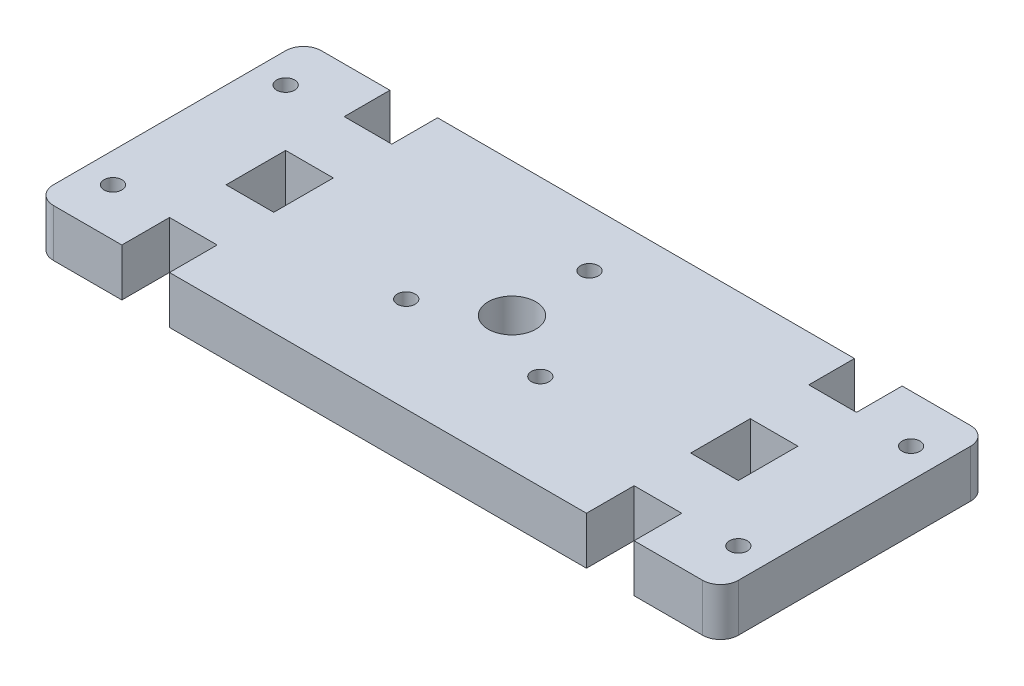
SolidWorks part; units mm, degrees
other "Markup1"
sketch "Sketch5" plane through (52.5, 8, -22.5) normal (0.067, 0.7574, -0.6495) x (-0.9884, -0.0385, -0.1469)
ref_plane "Front Plane" through (0, 0, 0) normal (0, 0, 1) x (1, 0, 0)
ref_plane "Top Plane" through (0, 0, 0) normal (0, 1, 0) x (1, 0, 0)
ref_plane "Right Plane" through (0, 0, 0) normal (1, 0, 0) x (0, 0, -1)
sketch "Sketch1" plane through (0, 0, 0) normal (0, 1, 0) x (1, 0, 0)
  line L0 (0, 0) -> (0, 1)
  line L1 (0, 1) -> (0, 25)
  line L3 (-57.5, -22.5) -> (57.5, -22.5)
  line L4 (-57.5, -22.5) -> (-57.5, 22.5)
  line L5 (-57.5, 22.5) -> (57.5, 22.5)
  line L6 (57.5, -22.5) -> (57.5, 22.5)
  line L7 (-57.5, -22.5) -> (57.5, 22.5) construction
  line L8 (-57.5, 22.5) -> (57.5, -22.5) construction
  circle A0 centre (0, 0) radius 50
  circle A1 centre (0, 0) radius 4
  circle A2 centre (0, 13) radius 1.5
  circle A3 centre (11.2583, -6.5) radius 1.5
  circle A4 centre (-11.2583, -6.5) radius 1.5
  dimension "D1" = 100
  dimension "D2" = 3
  dimension "D3" = 8
  dimension "D7" = 3
  dimension "D4" = 13
  dimension "D5" = 45
  dimension "125" = 115
extrude "Boss-Extrude1" add sketch "Sketch1" along normal blind 8
sketch "Sketch2" plane through (0, 8, 0) normal (0, 1, 0) x (1, 0, 0)
  line L1 (0, 0) -> (-35, 0)
  line L3 (-35, 0) -> (-35, 5)
  line L4 (-57.5, -22.5) -> (57.5, -22.5) construction
  line L12 (-35, 5) -> (-43, 5)
  line L13 (-35, 5) -> (-35, -5)
  line L18 (-35, -5) -> (-43, -5)
  line L27 (-43, 5) -> (-43, -5)
  line L55 (-35, 22.8298) -> (-43, 22.8298)
  line L56 (-35, 22.8298) -> (-35, 14.8298)
  line L57 (-35, 14.8298) -> (-43, 14.8298)
  line L58 (-43, 22.8298) -> (-43, 14.8298)
  line L63 (0, 0) -> (0, 22.8298)
  line L76 (43, 22.8298) -> (43, 14.8298)
  line L77 (35, 14.8298) -> (43, 14.8298)
  line L78 (35, 22.8298) -> (35, 14.8298)
  line L79 (35, 22.8298) -> (43, 22.8298)
  line L80 (43, 5) -> (43, -5)
  line L81 (35, -5) -> (43, -5)
  line L82 (35, 5) -> (35, -5)
  line L83 (35, 5) -> (43, 5)
  line L84 (35, 0) -> (35, 5)
  line L87 (-43, 0) -> (-49.5, 0)
  line L93 (-57.5, 0) -> (-56, 0)
  line L103 (-35, -22.5) -> (-43, -22.5)
  line L104 (-35, -22.5) -> (-35, -14.5)
  line L105 (-35, -14.5) -> (-43, -14.5)
  line L106 (-43, -22.5) -> (-43, -14.5)
  line L108 (35, -22.5) -> (43, -22.5)
  line L109 (35, -22.5) -> (35, -14.5)
  line L110 (35, -14.5) -> (43, -14.5)
  line L111 (43, -22.5) -> (43, -14.5)
  line L114 (-57.5, -22.5) -> (-57.5, 22.5) construction
  line L115 (-56, 0) -> (-56, -4)
  line L116 (56, 4) -> (49.5, 4)
  line L117 (-56, -4) -> (-49.5, -4)
  line L118 (-56, -4) -> (-56, 4)
  line L119 (-56, 4) -> (-49.5, 4)
  line L120 (-49.5, -4) -> (-49.5, 4)
  line L121 (49.5, -4) -> (49.5, 4)
  line L122 (56, -4) -> (49.5, -4)
  line L123 (56, -4) -> (56, 4)
  line L124 (56, 0) -> (56, -4)
  dimension "D2" = 35
  dimension "D3" = 8
  dimension "D6" = 0
extrude "Cut-Extrude1" cut sketch "Sketch2" against normal blind 16
fillet "Fillet1" radius 3 4 edges at (57.5, 4, -22.5) (57.5, 4, 22.5) (-57.5, 4, -22.5) (-57.5, 4, 22.5)
sketch "Sketch4" plane through (0, 8, 0) normal (0, 1, 0) x (1, 0, 0)
  line L1 (43, 22.5) -> (54.5, 22.5) construction
  line L2 (57.5, -19.5) -> (57.5, 19.5) construction
  circle A4 centre (52.5, 14.5) radius 1.5
  circle A5 centre (-52.5, 14.5) radius 1.5
  circle A6 centre (-52.5, -14.5) radius 1.5
  circle A7 centre (52.5, -14.5) radius 1.5
  dimension "D1" = 3
  dimension "D2" = 8
  dimension "D3" = 5
  dimension "D4" = 2
  dimension "D5" = 2
extrude "Cut-Extrude2" cut sketch "Sketch4" against normal blind 16
